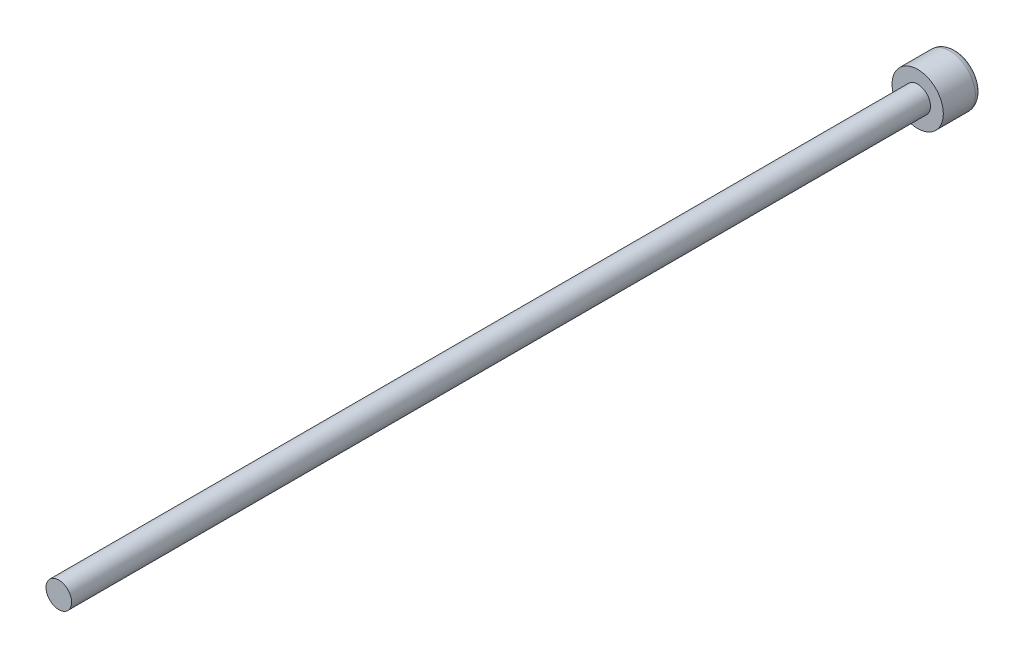
SolidWorks part; units mm, degrees
ref_plane "Front Plane" through (0, 0, 0) normal (0, 0, 1) x (1, 0, 0)
ref_plane "Top Plane" through (0, 0, 0) normal (0, 1, 0) x (1, 0, 0)
ref_plane "Right Plane" through (0, 0, 0) normal (1, 0, 0) x (0, 0, -1)
sketch "Sketch1" plane through (0, 0, 0) normal (0, 0, 1) x (1, 0, 0)
  circle A0 centre (0, 0) radius 1
  dimension "D1" = 2
extrude "Boss-Extrude1" add sketch "Sketch1" along normal blind 70
sketch "Sketch2" plane through (0, 0, 0) normal (0, 0, 1) x (1, 0, 0)
  circle A0 centre (0, 0) radius 2
  dimension "D1" = 4
extrude "Boss-Extrude2" add sketch "Sketch2" along normal blind 3
fillet "Fillet1" radius 0.5 1 edges at (2, 0, 0)
